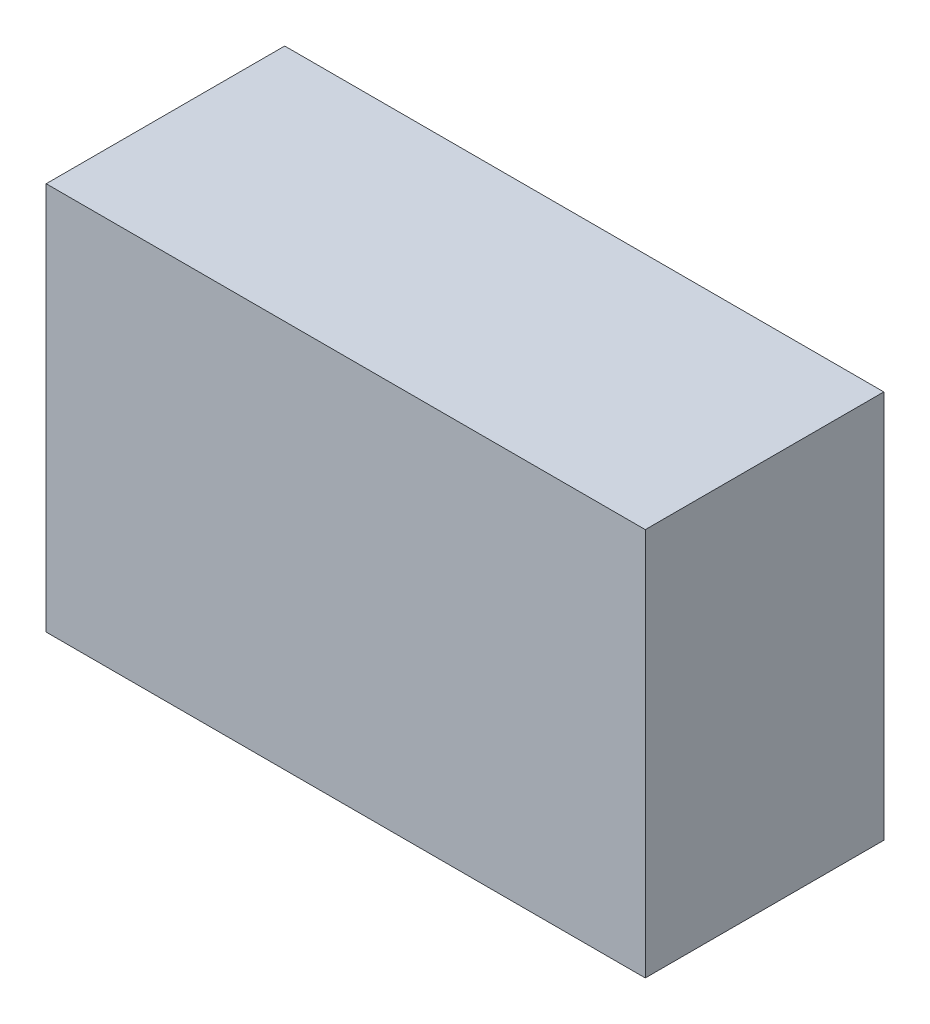
SolidWorks part; units mm, degrees
ref_plane "Front Plane" through (0, 0, 0) normal (0, 0, 1) x (1, 0, 0)
ref_plane "Top Plane" through (0, 0, 0) normal (0, 1, 0) x (1, 0, 0)
ref_plane "Right Plane" through (0, 0, 0) normal (1, 0, 0) x (0, 0, -1)
sketch "ｽｹｯﾁ1" plane through (0, 0, 0) normal (0, 0, 1) x (1, 0, 0)
  line L1 (-27, -17.5) -> (27, -17.5)
  line L2 (-27, -17.5) -> (-27, 17.5)
  line L3 (-27, 17.5) -> (27, 17.5)
  line L4 (27, -17.5) -> (27, 17.5)
  line L5 (-27, -17.5) -> (27, 17.5) construction
  line L6 (-27, 17.5) -> (27, -17.5) construction
  point P0 (0, 0)
  dimension "D1" = 54
  dimension "D2" = 35
extrude "ﾎﾞｽ - 押し出し1" add sketch "ｽｹｯﾁ1" along normal blind 21.5
